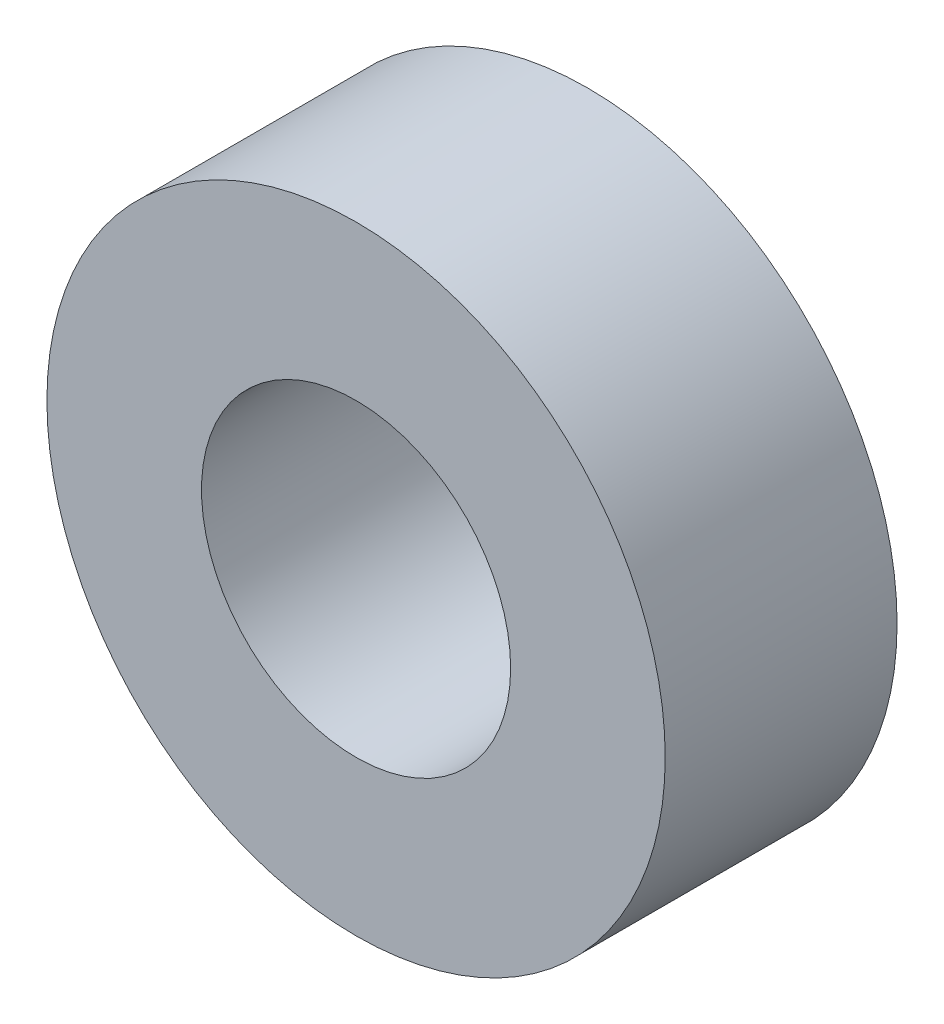
SolidWorks part; units mm, degrees
ref_plane "Front Plane" through (0, 0, 0) normal (0, 0, 1) x (1, 0, 0)
ref_plane "Top Plane" through (0, 0, 0) normal (0, 1, 0) x (1, 0, 0)
ref_plane "Right Plane" through (0, 0, 0) normal (1, 0, 0) x (0, 0, -1)
sketch "Sketch1" plane through (0, 0, 0) normal (0, 0, 1) x (1, 0, 0)
  circle A0 centre (0, 0) radius 6.35
  dimension "D1" = 12.7
extrude "Boss-Extrude1" add sketch "Sketch1" along normal blind 4.7625
sketch "Sketch2" plane through (0, 0, 4.7625) normal (0, 0, 1) x (1, 0, 0)
  circle A0 centre (0, 0) radius 3.175
  dimension "D1" = 6.35
extrude "Cut-Extrude1" cut sketch "Sketch2" against normal through all both and the other way through all
